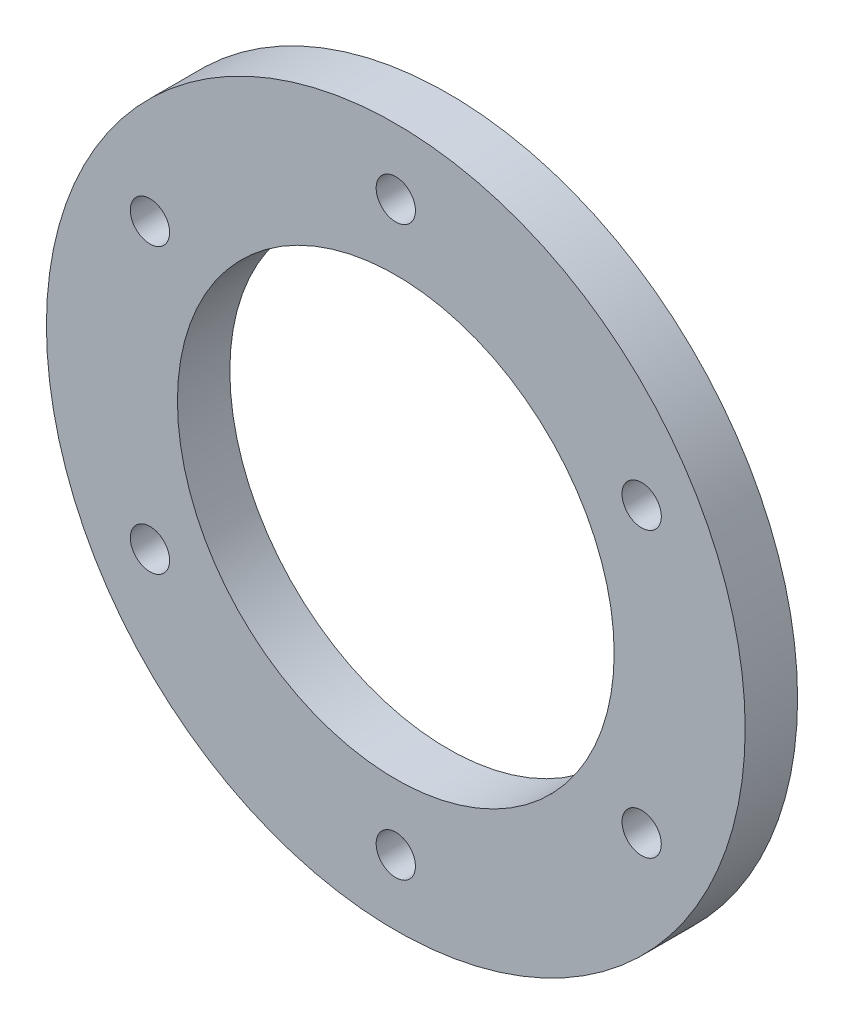
SolidWorks part; units mm, degrees
material "AISI 316 Stainless Steel Sheet (SS)"
ref_plane "Front Plane" through (0, 0, 0) normal (0, 0, 1) x (1, 0, 0)
ref_plane "Top Plane" through (0, 0, 0) normal (0, 1, 0) x (1, 0, 0)
ref_plane "Right Plane" through (0, 0, 0) normal (1, 0, 0) x (0, 0, -1)
sketch "Sketch1" plane through (0, 0, 0) normal (0, 0, 1) x (1, 0, 0)
  circle A0 centre (0, 0) radius 40
  circle A1 centre (0, 0) radius 25
  dimension "D1" = 80
  dimension "D2" = 50
extrude "Boss-Extrude1" add sketch "Sketch1" along normal blind 6
sketch "Sketch2" plane through (0, 0, 0) normal (0, 0, 1) x (1, 0, 0)
  circle A0 centre (0, 0) radius 32.5 construction
  circle A3 centre (0, 32.5) radius 2.25
  dimension "D1" = 65
  dimension "D2" = 4.5
extrude "Cut-Extrude1" cut sketch "Sketch2" along normal through all
pattern_circular "CirPattern1" count 6 over 360 about axis through (0, 0, 6) along (0, 0, 1) of "Cut-Extrude1"
